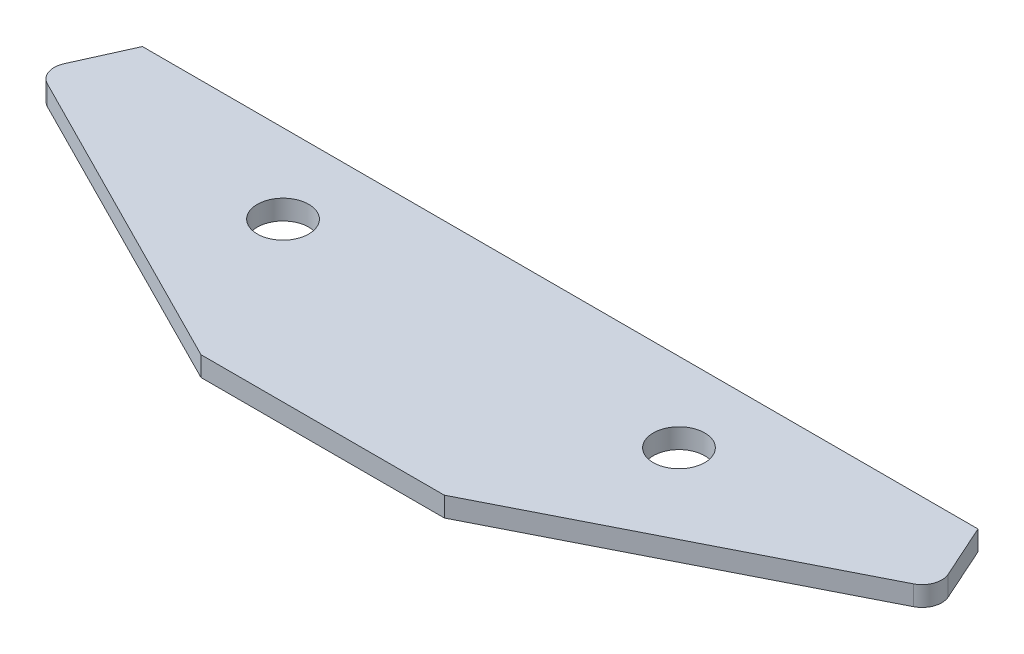
SolidWorks part; units mm, degrees
material "ASTM A36 Steel"
ref_plane "Front Plane" through (0, 0, 0) normal (0, 0, 1) x (1, 0, 0)
ref_plane "Top Plane" through (0, 0, 0) normal (0, 1, 0) x (1, 0, 0)
ref_plane "Right Plane" through (0, 0, 0) normal (1, 0, 0) x (0, 0, -1)
sketch "Sketch1" plane through (0, 0, 0) normal (0, 1, 0) x (1, 0, 0)
  line L0 (248.0329, 52.5933) -> (260.3056, 25.2785)
  line L1 (41.5206, -96.2553) -> (255.7035, 12.2597)
  line L8 (32.4816, -96.2553) -> (-181.7012, 12.2597)
  line L9 (-174.0307, 52.5933) -> (-186.3033, 25.2785)
  line L10 (-174.0307, 52.5933) -> (248.0329, 52.5933)
  arc A0 (260.3056, 25.2785) -> (255.7035, 12.2597) centre (251.184, 21.1802) cw
  arc A1 (32.4816, -96.2553) -> (41.5206, -96.2553) centre (37.0011, -87.3348) ccw
  arc A5 (-186.3033, 25.2785) -> (-181.7012, 12.2597) centre (-177.1817, 21.1802) ccw
  point P18 (-190.2147, 16.5731)
  dimension "D1" = 10
extrude "Boss-Extrude1" add sketch "Sketch1" along normal blind 10
sketch "Sketch2" plane through (0, 10, 0) normal (0, 1, 0) x (1, 0, 0)
  line L0 (248.0329, 52.5933) -> (-174.0307, 52.5933) construction
  circle A0 centre (137.0011, 12.5933) radius 13
  circle A1 centre (-62.9989, 12.5933) radius 13
  point P6 (37.0011, 52.5933)
  dimension "D1" = 26
  dimension "D2" = 100
  dimension "D3" = 40
  dimension "D4" = 26
  dimension "D5" = 40
  dimension "D6" = 100
extrude "Cut-Extrude1" cut sketch "Sketch2" against normal blind 10
sketch "Sketch3" plane through (0, 10, 0) normal (0, 1, 0) x (1, 0, 0)
  line L2 (37.0011, -67.4067) -> (125.4591, -67.4067)
  line L3 (37.0011, -67.4067) -> (-80.9428, -67.4067)
  line L4 (-80.9428, -67.4067) -> (-80.9428, -160.4734)
  line L5 (-80.9428, -160.4734) -> (125.4591, -160.4734)
  line L6 (125.4591, -160.4734) -> (125.4591, -67.4067)
extrude "Cut-Extrude2" cut sketch "Sketch3" against normal blind 10
